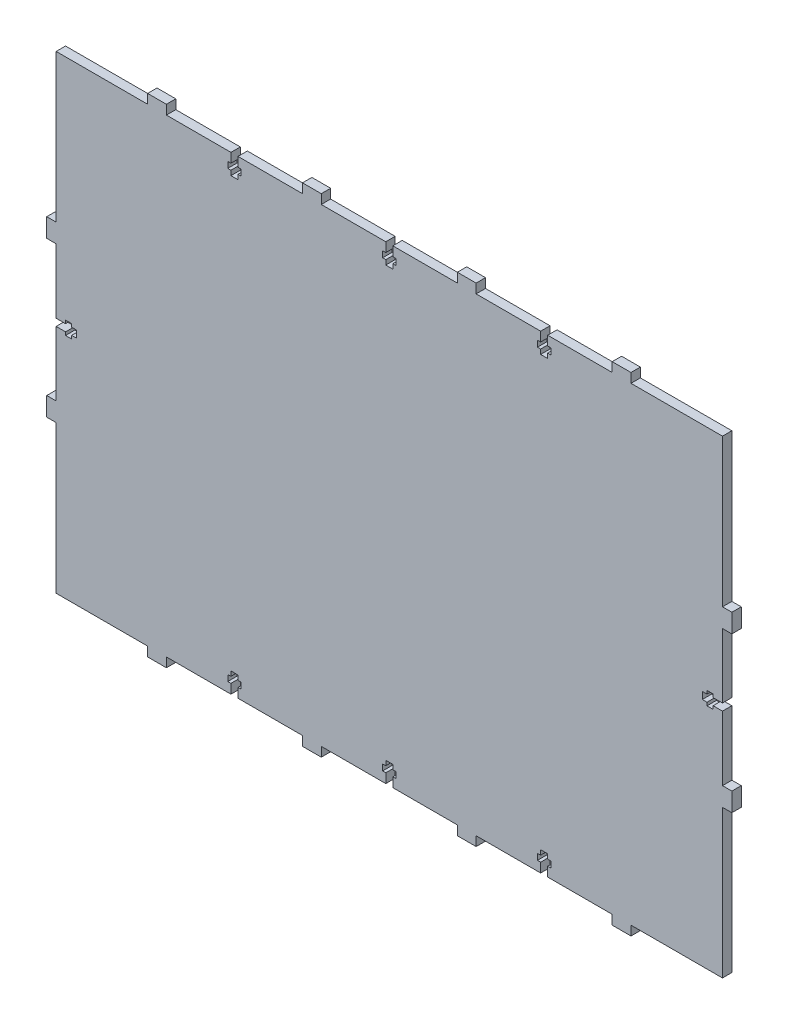
SolidWorks part; units mm, degrees
ref_plane "前视基准面" through (0, 0, 0) normal (0, 0, 1) x (1, 0, 0)
ref_plane "上视基准面" through (0, 0, 0) normal (0, 1, 0) x (1, 0, 0)
ref_plane "右视基准面" through (0, 0, 0) normal (1, 0, 0) x (0, 0, -1)
sketch "草图1" plane through (0, 0, 0) normal (0, 0, 1) x (1, 0, 0)
  line L0 (0, 0) -> (0, -4)
  line L1 (0, -4) -> (-1.35, -4)
  line L2 (-1.35, -4) -> (-1.35, -6.6)
  line L3 (-1.35, -6.6) -> (0, -6.6)
  line L4 (0, -6.6) -> (0, -8.6)
  line L5 (0, -8.6) -> (3, -8.6)
  line L6 (3, -8.6) -> (3, -6.6)
  line L7 (3, -6.6) -> (4.35, -6.6)
  line L8 (4.35, -6.6) -> (4.35, -4)
  line L9 (4.35, -4) -> (3, -4)
  line L10 (3, -4) -> (3, 0)
  line L11 (0, 0) -> (-27.5, 0)
  line L12 (-27.5, 0) -> (-27.5, 4)
  line L13 (-27.5, 4) -> (-35.5, 4)
  line L14 (-35.5, 4) -> (-35.5, 0)
  line L15 (1.5, -8.6) -> (1.5, -6.6) construction
  line L16 (-31.5, 4) -> (-31.5, -50) construction
  line L17 (-67.35, -4) -> (-66, -4)
  line L18 (-66, -6.6) -> (-67.35, -6.6)
  line L19 (-61.65, -6.6) -> (-63, -6.6)
  line L20 (-63, -4) -> (-61.65, -4)
  line L21 (-66, -4) -> (-66, 0)
  line L22 (-66, -8.6) -> (-66, -6.6)
  line L23 (-63, -8.6) -> (-66, -8.6)
  line L24 (-63, -6.6) -> (-63, -8.6)
  line L25 (-67.35, -6.6) -> (-67.35, -4)
  line L26 (-61.65, -4) -> (-61.65, -6.6)
  line L27 (-63, 0) -> (-63, -4)
  line L28 (-63, 0) -> (-35.5, 0)
  line L29 (30.5, 4) -> (38.5, 4)
  line L30 (30.5, 0) -> (30.5, 4)
  line L31 (38.5, 4) -> (38.5, 0)
  line L32 (3, 0) -> (30.5, 0)
  line L33 (66, 0) -> (38.5, 0)
  line L34 (66, 0) -> (66, -4)
  line L35 (64.65, -4) -> (64.65, -6.6)
  line L36 (70.35, -6.6) -> (70.35, -4)
  line L37 (66, -6.6) -> (66, -8.6)
  line L38 (66, -8.6) -> (69, -8.6)
  line L39 (69, -8.6) -> (69, -6.6)
  line L40 (69, -4) -> (69, 0)
  line L41 (66, -4) -> (64.65, -4)
  line L42 (64.65, -6.6) -> (66, -6.6)
  line L43 (69, -6.6) -> (70.35, -6.6)
  line L44 (70.35, -4) -> (69, -4)
  line L45 (67.5, -8.6) -> (67.5, -6.6) construction
  line L46 (69, 0) -> (96.5, 0)
  line L47 (132, 0) -> (104.5, 0)
  line L48 (96.5, 4) -> (96.5, 0)
  line L49 (104.5, 0) -> (104.5, 4)
  line L50 (104.5, 4) -> (96.5, 4)
  line L51 (-64.5, -8.6) -> (-64.5, -6.6) construction
  line L52 (-97.5, 4) -> (-97.5, -50) construction
  line L53 (-66, 0) -> (-93.5, 0)
  line L54 (-93.5, 4) -> (-93.5, 0)
  line L55 (-101.5, 4) -> (-93.5, 4)
  line L56 (-101.5, 0) -> (-101.5, 4)
  line L57 (-129, 0) -> (-101.5, 0)
  line L58 (1.5, -8.6) -> (-140.5, -8.6) construction
  line L59 (-129, 0) -> (-140.5, 0)
  line L60 (132, 0) -> (143.5, 0)
  line L63 (143.5, -200) -> (143.5, 0) construction
  line L64 (143.5, -100) -> (115.133, -100) construction
  line L65 (-129, -200) -> (-140.5, -200)
  line L66 (1.5, -191.4) -> (1.5, -193.4) construction
  line L67 (3, -196) -> (3, -200)
  line L68 (4.35, -196) -> (3, -196)
  line L69 (4.35, -193.4) -> (4.35, -196)
  line L70 (3, -193.4) -> (4.35, -193.4)
  line L71 (3, -191.4) -> (3, -193.4)
  line L72 (0, -191.4) -> (3, -191.4)
  line L73 (0, -193.4) -> (0, -191.4)
  line L74 (-1.35, -193.4) -> (0, -193.4)
  line L75 (-1.35, -196) -> (-1.35, -193.4)
  line L76 (0, -196) -> (-1.35, -196)
  line L77 (0, -200) -> (0, -196)
  line L78 (132, -200) -> (143.5, -200)
  line L79 (67.5, -191.4) -> (67.5, -193.4) construction
  line L80 (104.5, -204) -> (96.5, -204)
  line L81 (104.5, -200) -> (104.5, -204)
  line L82 (96.5, -204) -> (96.5, -200)
  line L83 (132, -200) -> (104.5, -200)
  line L84 (69, -200) -> (96.5, -200)
  line L85 (70.35, -196) -> (69, -196)
  line L86 (69, -193.4) -> (70.35, -193.4)
  line L87 (64.65, -193.4) -> (66, -193.4)
  line L88 (66, -196) -> (64.65, -196)
  line L89 (69, -196) -> (69, -200)
  line L90 (69, -191.4) -> (69, -193.4)
  line L91 (66, -191.4) -> (69, -191.4)
  line L92 (66, -193.4) -> (66, -191.4)
  line L93 (70.35, -193.4) -> (70.35, -196)
  line L94 (64.65, -196) -> (64.65, -193.4)
  line L95 (66, -200) -> (66, -196)
  line L96 (66, -200) -> (38.5, -200)
  line L97 (3, -200) -> (30.5, -200)
  line L98 (38.5, -204) -> (38.5, -200)
  line L99 (30.5, -200) -> (30.5, -204)
  line L100 (30.5, -204) -> (38.5, -204)
  line L101 (1.5, -191.4) -> (-140.5, -191.4) construction
  line L102 (-97.5, -204) -> (-97.5, -150) construction
  line L103 (-64.5, -191.4) -> (-64.5, -193.4) construction
  line L104 (-31.5, -204) -> (-31.5, -150) construction
  line L105 (-129, -200) -> (-101.5, -200)
  line L106 (-101.5, -200) -> (-101.5, -204)
  line L107 (-101.5, -204) -> (-93.5, -204)
  line L108 (-93.5, -204) -> (-93.5, -200)
  line L109 (-66, -200) -> (-93.5, -200)
  line L110 (-63, -200) -> (-35.5, -200)
  line L111 (-63, -200) -> (-63, -196)
  line L112 (-61.65, -196) -> (-61.65, -193.4)
  line L113 (-67.35, -193.4) -> (-67.35, -196)
  line L114 (-63, -193.4) -> (-63, -191.4)
  line L115 (-63, -191.4) -> (-66, -191.4)
  line L116 (-66, -191.4) -> (-66, -193.4)
  line L117 (-66, -196) -> (-66, -200)
  line L118 (-63, -196) -> (-61.65, -196)
  line L119 (-61.65, -193.4) -> (-63, -193.4)
  line L120 (-66, -193.4) -> (-67.35, -193.4)
  line L121 (-67.35, -196) -> (-66, -196)
  line L122 (-35.5, -204) -> (-35.5, -200)
  line L123 (-27.5, -204) -> (-35.5, -204)
  line L124 (-27.5, -200) -> (-27.5, -204)
  line L125 (0, -200) -> (-27.5, -200)
  line L126 (143.5, -98.5) -> (139.5, -98.5)
  line L127 (139.5, -98.5) -> (139.5, -97.15)
  line L128 (139.5, -97.15) -> (136.9, -97.15)
  line L129 (136.9, -97.15) -> (136.9, -98.5)
  line L130 (136.9, -98.5) -> (134.9, -98.5)
  line L131 (134.9, -98.5) -> (134.9, -101.5)
  line L132 (134.9, -101.5) -> (136.9, -101.5)
  line L133 (136.9, -101.5) -> (136.9, -102.85)
  line L134 (136.9, -102.85) -> (139.5, -102.85)
  line L135 (139.5, -102.85) -> (139.5, -101.5)
  line L136 (139.5, -101.5) -> (143.5, -101.5)
  line L137 (134.9, -100) -> (143.5, -100) construction
  line L138 (147.5, -67) -> (143.5, -67) construction
  line L139 (143.5, -71) -> (147.5, -71)
  line L140 (147.5, -71) -> (147.5, -63)
  line L141 (147.5, -63) -> (143.5, -63)
  line L142 (147.5, -133) -> (143.5, -133) construction
  line L143 (147.5, -137) -> (143.5, -137)
  line L144 (147.5, -129) -> (147.5, -137)
  line L145 (143.5, -129) -> (147.5, -129)
  line L146 (143.5, -98.5) -> (143.5, -71)
  line L147 (143.5, -101.5) -> (143.5, -129)
  line L148 (143.5, -137) -> (143.5, -200)
  line L149 (143.5, -63) -> (143.5, 0)
  line L150 (-144.5, -133) -> (-140.5, -133) construction
  line L151 (-144.5, -67) -> (-140.5, -67) construction
  line L154 (-140.5, -101.5) -> (-140.5, -129)
  line L155 (-140.5, -98.5) -> (-140.5, -71)
  line L156 (-140.5, -129) -> (-144.5, -129)
  line L157 (-144.5, -129) -> (-144.5, -137)
  line L158 (-144.5, -137) -> (-140.5, -137)
  line L159 (-144.5, -63) -> (-140.5, -63)
  line L160 (-144.5, -71) -> (-144.5, -63)
  line L161 (-140.5, -71) -> (-144.5, -71)
  line L162 (-136.5, -101.5) -> (-140.5, -101.5)
  line L163 (-136.5, -102.85) -> (-136.5, -101.5)
  line L164 (-133.9, -102.85) -> (-136.5, -102.85)
  line L165 (-133.9, -101.5) -> (-133.9, -102.85)
  line L166 (-131.9, -101.5) -> (-133.9, -101.5)
  line L167 (-131.9, -98.5) -> (-131.9, -101.5)
  line L168 (-133.9, -98.5) -> (-131.9, -98.5)
  line L169 (-133.9, -97.15) -> (-133.9, -98.5)
  line L170 (-136.5, -97.15) -> (-133.9, -97.15)
  line L171 (-136.5, -98.5) -> (-136.5, -97.15)
  line L172 (-140.5, -98.5) -> (-136.5, -98.5)
  line L173 (-140.5, 0) -> (-140.5, -63)
  line L174 (-140.5, -200) -> (-140.5, -137)
  dimension "D1" = 3
  dimension "D2" = 2
  dimension "D3" = 4
  dimension "D4" = 2.6
  dimension "D5" = 1.35
  dimension "D6" = 200
  dimension "D7" = 4
  dimension "D8" = 284
  dimension "D9" = 3
  dimension "D10" = 2
  dimension "D11" = 2.6
  dimension "D12" = 1.35
  dimension "D13" = 8
  dimension "D14" = 4
  dimension "D15" = 29
extrude "凸台-拉伸1" add sketch "草图1" along normal blind 4 contours L33 L31 L29 L30 L32 L10 L9 L8 L7 L6 L5 L4 L3 L2 L1 L0 L11 L12 L13 L14 L28 L27 L20 L26 L19 L24 L23 L22 L18 L25 L17 L21 L53 L54 L55 L56 L57 L59 L173 L159 L160 L161 L155 L172 L171 L170 L169 L168 L167 L166 L165 L164 L163 L162 L154 L156 L157 L158 L174 L65 L105 L106 L107 L108 L109 L117 L121 L113 L120 L116 L115 L114 L119 L112 L118 L111 L110 L122 L123 L124 L125 L77 L76 L75 L74 L73 L72 L71 L70 L69 L68 L67 L97 L99 L100 L98 L96 L95 L88 L94 L87 L92 L91 L90 L86 L93 L85 L89 L84 L82 L80 L81 L83 L78 L148 L143 L144 L145 L147 L136 L135 L134 L133 L132 L131 L130 L129 L128 L127 L126 L146 L139 L140 L141 L149 L60 L47 L49 L50 L48 L46 L40 L44 L36 L43 L39 L38 L37 L42 L35 L41 L34
sketch "草图2" plane through (0, -200, 0) normal (0, -1, 0) x (1, 0, 0)
  line L0 (0, 2) -> (3, 2)
  line L1 (0, 4) -> (0, 0) construction
  line L2 (3, 4) -> (3, 0) construction
  circle A0 centre (1.5, 2) radius 1.5
sketch "草图3" plane through (0, 0, 0) normal (0, 1, 0) x (1, 0, 0)
  line L0 (0, -2) -> (3, -2)
  line L1 (0, -4) -> (0, 0) construction
  line L2 (3, -4) -> (3, 0) construction
  circle A0 centre (1.5, -2) radius 1.5
